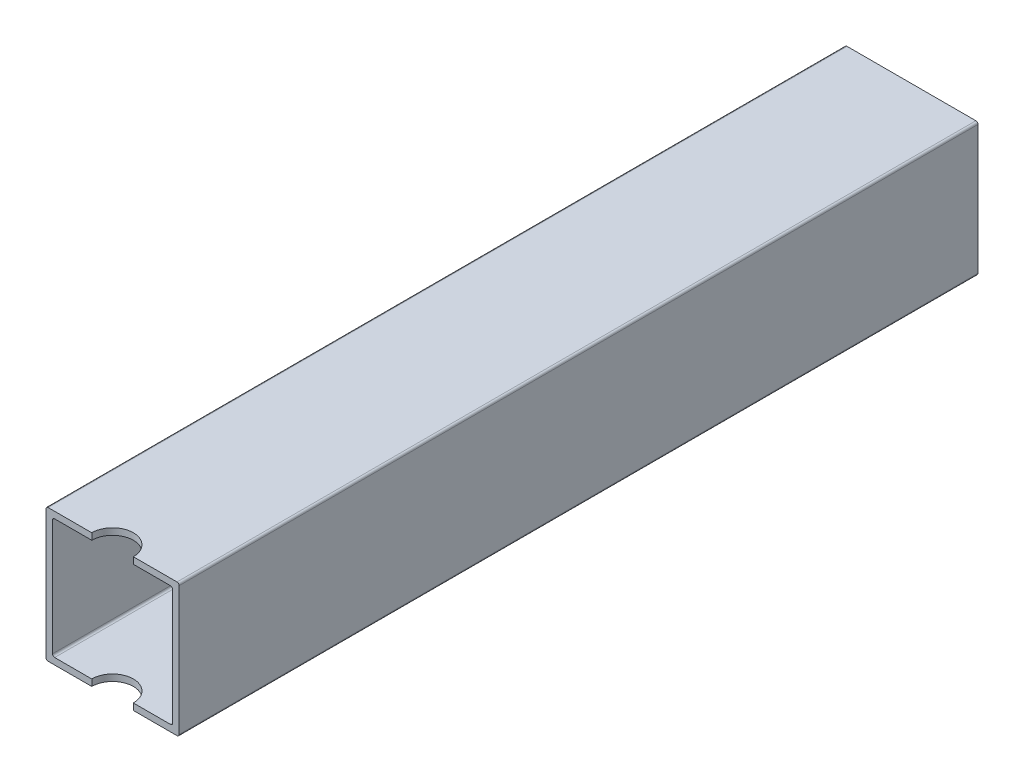
SolidWorks part; units mm, degrees
ref_plane "Front Plane" through (0, 0, 0) normal (0, 0, 1) x (1, 0, 0)
ref_plane "Top Plane" through (0, 0, 0) normal (0, 1, 0) x (1, 0, 0)
ref_plane "Right Plane" through (0, 0, 0) normal (1, 0, 0) x (0, 0, -1)
sketch "Sketch1" plane through (0, 0, 0) normal (0, 0, 1) x (1, 0, 0)
  line L1 (0, 0) -> (25.4, 0)
  line L2 (0, 0) -> (0, 25.4)
  line L3 (0, 25.4) -> (25.4, 25.4)
  line L4 (25.4, 0) -> (25.4, 25.4)
  line L5 (1.2446, 1.2446) -> (24.1554, 1.2446)
  line L6 (1.2446, 1.2446) -> (1.2446, 24.1554)
  line L7 (1.2446, 24.1554) -> (24.1554, 24.1554)
  line L8 (24.1554, 1.2446) -> (24.1554, 24.1554)
  dimension "D1" = 1.2446
  dimension "D2" = 1.2446
  dimension "D3" = 25.4
  dimension "D4" = 1.2446
extrude "Boss-Extrude1" add sketch "Sketch1" against normal blind 152.4
fillet "Fillet1" radius 0.4064 4 edges at (0, 0, -76.2) (25.4, 0, -76.2) (0, 25.4, -76.2) (25.4, 25.4, -76.2)
fillet "Fillet2" radius 0.4064 4 edges at (1.2446, 24.1554, -76.2) (24.1554, 24.1554, -76.2) (24.1554, 1.2446, -76.2) (1.2446, 1.2446, -76.2)
sketch "Sketch2" plane through (0, 25.4, 0) normal (0, 1, 0) x (1, 0, 0)
  line L0 (24.9936, 0) -> (0.4064, 0) construction
  circle A0 centre (12.7, 0) radius 3.9688
  dimension "D1" = 7.9375
extrude "Cut-Extrude1" cut sketch "Sketch2" against normal through all
